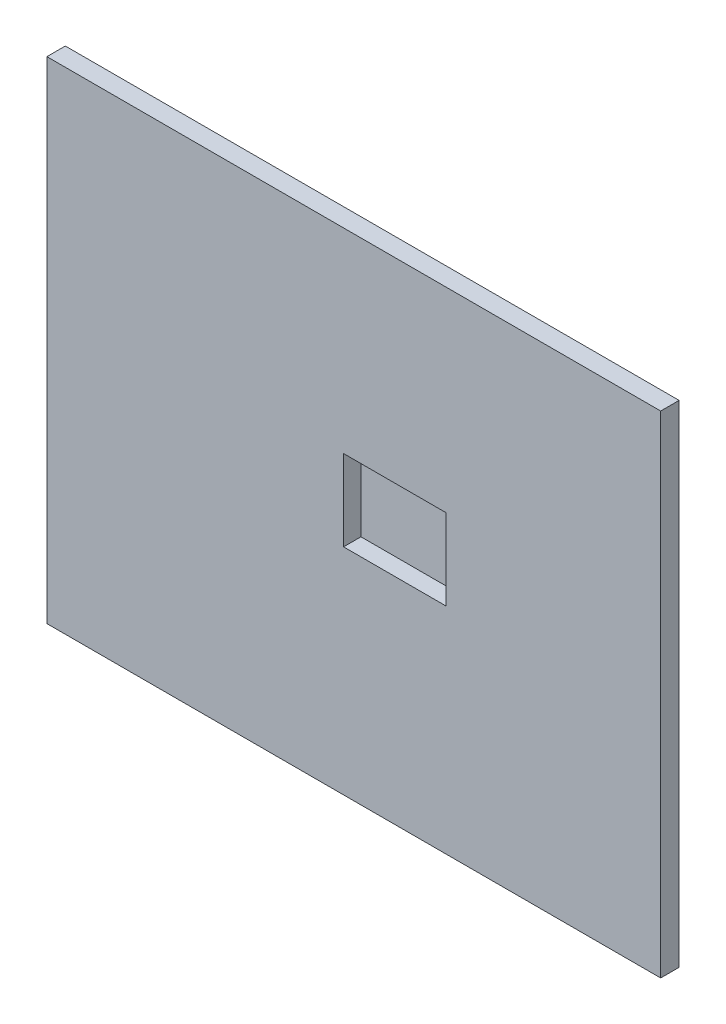
SolidWorks part; units mm, degrees
ref_plane "Plan de face" through (0, 0, 0) normal (0, 0, 1) x (1, 0, 0)
ref_plane "Plan de dessus" through (0, 0, 0) normal (0, 1, 0) x (1, 0, 0)
ref_plane "Plan de droite" through (0, 0, 0) normal (1, 0, 0) x (0, 0, -1)
sketch "Esquisse1" plane through (0, 0, 0) normal (0, 0, 1) x (1, 0, 0)
  line L1 (-300, 240) -> (300, 240)
  line L2 (-300, 240) -> (-300, -240)
  line L3 (-300, -240) -> (300, -240)
  line L4 (300, 240) -> (300, -240)
  line L5 (-300, 240) -> (300, -240) construction
  line L6 (-300, -240) -> (300, 240) construction
  point P0 (0, 0)
  dimension "D1" = 600
  dimension "D2" = 480
extrude "Boss.-Extru.1" add sketch "Esquisse1" along normal blind 18
sketch "Esquisse2" plane through (0, 0, 18) normal (0, 0, 1) x (1, 0, 0)
  line L0 (300, -240) -> (300, 240) construction
  line L1 (-10, -30) -> (90, -30)
  line L2 (-10, -30) -> (-10, 49)
  line L3 (-10, 49) -> (90, 49)
  line L4 (90, -30) -> (90, 49)
  line L5 (-300, -240) -> (300, -240) construction
  dimension "D1" = 210
  dimension "D2" = 210
  dimension "D3" = 100
  dimension "D4" = 79
extrude "Enlèv. mat.-Extru.1" cut sketch "Esquisse2" against normal blind 17
